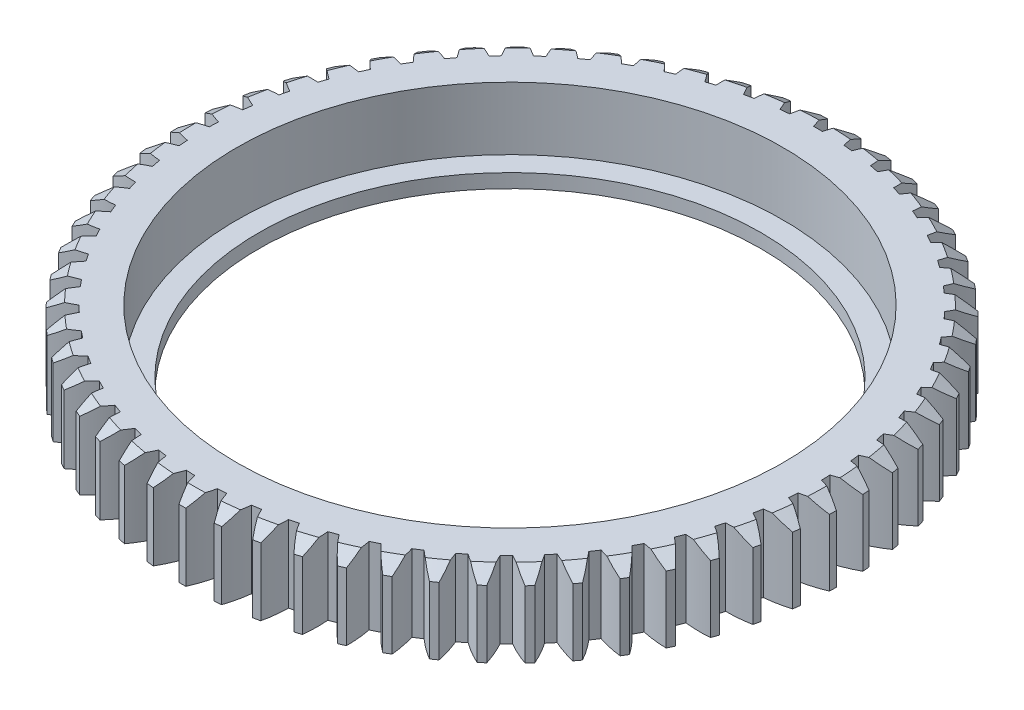
SolidWorks part; units mm, degrees
ref_plane "Front Plane" through (0, 0, 0) normal (0, 0, 1) x (1, 0, 0)
ref_plane "Top Plane" through (0, 0, 0) normal (0, 1, 0) x (1, 0, 0)
ref_plane "Right Plane" through (0, 0, 0) normal (1, 0, 0) x (0, 0, -1)
sketch "Sketch1" plane through (0, 0, 0) normal (0, 1, 0) x (1, 0, 0)
  circle A0 centre (0, 0) radius 47.5
  dimension "D1" = 95
extrude "Boss-Extrude1" add sketch "Sketch1" along normal blind 11 contours A0
sketch "Sketch2" plane through (0, 11, 0) normal (0, 1, 0) x (1, 0, 0)
  circle A0 centre (0, 0) radius 39.15
  dimension "D1" = 78.3
extrude "Cut-Extrude1" cut sketch "Sketch2" against normal blind 9 contours A0
sketch "Sketch3" plane through (0, 2, 0) normal (0, 1, 0) x (1, 0, 0)
  circle A0 centre (0, 0) radius 36
  dimension "D1" = 72
extrude "Cut-Extrude2" cut sketch "Sketch3" against normal through all
sketch "Sketch4" plane through (0, 11, 0) normal (0, 1, 0) x (1, 0, 0)
  arc A0 (-46.9496, 3.2406) -> (-43.6435, 1.852) centre (-38.2442, 19.3373) ccw
  arc A1 (-43.6435, 1.852) -> (-43.6763, 0.577) centre (0.1949, 0.0849) ccw
  arc A2 (-43.6763, 0.577) -> (-47.0495, -0.6396) centre (-39.1843, -17.1632) ccw
  arc A3 (-47.0495, -0.6396) -> (-47.0242, -1.6236) centre (0.1949, 0.0849) ccw
  arc A4 (-47.0242, -1.6236) -> (-43.5928, -2.6649) centre (-40.02, 15.2829) ccw
  arc A5 (-43.5928, -2.6649) -> (-43.4944, -3.9365) centre (0.1949, 0.0849) ccw
  arc A6 (-43.4944, -3.9365) -> (-46.7246, -5.4935) centre (-37.2021, -21.1208) ccw
  arc A7 (-46.7246, -5.4935) -> (-46.5982, -6.4697) centre (0.1949, 0.0849) ccw
  arc A8 (-46.5982, -6.4697) -> (-43.078, -7.1526) centre (-41.3695, 11.0675) ccw
  arc A9 (-43.078, -7.1526) -> (-42.8493, -8.4074) centre (0.1949, 0.0849) ccw
  arc A10 (-42.8493, -8.4074) -> (-45.9023, -10.2882) centre (-34.8235, -24.8536) ccw
  arc A11 (-45.9023, -10.2882) -> (-45.6763, -11.2463) centre (0.1949, 0.0849) ccw
  arc A12 (-45.6763, -11.2463) -> (-42.1045, -11.5636) centre (-42.2785, 6.7355) ccw
  arc A13 (-42.1045, -11.5636) -> (-41.748, -12.7882) centre (0.1949, 0.0849) ccw
  arc A14 (-41.748, -12.7882) -> (-44.5914, -14.973) centre (-32.0737, -28.322) ccw
  arc A15 (-44.5914, -14.973) -> (-44.268, -15.9027) centre (0.1949, 0.0849) ccw
  arc A16 (-44.268, -15.9027) -> (-40.6825, -15.8512) centre (-42.7372, 2.3331) ccw
  arc A17 (-40.6825, -15.8512) -> (-40.202, -17.0326) centre (0.1949, 0.0849) ccw
  arc A18 (-40.202, -17.0326) -> (-42.8058, -19.4982) centre (-28.9818, -31.4894) ccw
  arc A19 (-42.8058, -19.4982) -> (-42.3885, -20.3897) centre (0.1949, 0.0849) ccw
  arc A20 (-42.3885, -20.3897) -> (-38.8273, -19.9698) centre (-42.7408, -2.0931) ccw
  arc A21 (-38.8273, -19.9698) -> (-38.2279, -21.0956) centre (0.1949, 0.0849) ccw
  arc A22 (-38.2279, -21.0956) -> (-40.5643, -23.8158) centre (-25.5807, -34.322) ccw
  arc A23 (-40.5643, -23.8158) -> (-40.0576, -24.6597) centre (0.1949, 0.0849) ccw
  arc A24 (-40.0576, -24.6597) -> (-36.5585, -23.8758) centre (-42.2893, -6.4963) ccw
  arc A25 (-36.5585, -23.8758) -> (-35.8465, -24.934) centre (0.1949, 0.0849) ccw
  arc A26 (-35.8465, -24.934) -> (-37.8908, -27.88) centre (-21.9063, -36.7899) ccw
  arc A27 (-37.8908, -27.88) -> (-37.3, -28.6673) centre (0.1949, 0.0849) ccw
  arc A28 (-37.3, -28.6673) -> (-33.9, -27.5278) centre (-41.3874, -10.8296) ccw
  arc A29 (-33.9, -27.5278) -> (-33.083, -28.5072) centre (0.1949, 0.0849) ccw
  arc A30 (-33.083, -28.5072) -> (-34.8136, -31.6478) centre (-17.9977, -38.867) ccw
  arc A31 (-34.8136, -31.6478) -> (-34.1449, -32.3702) centre (0.1949, 0.0849) ccw
  arc A32 (-34.1449, -32.3702) -> (-30.8801, -30.8871) centre (-40.0448, -15.0473) ccw
  arc A33 (-30.8801, -30.8871) -> (-29.9667, -31.7773) centre (0.1949, 0.0849) ccw
  arc A34 (-29.9667, -31.7773) -> (-31.3652, -35.0792) centre (-13.8962, -40.5311) ccw
  arc A35 (-31.3652, -35.0792) -> (-30.6259, -35.729) centre (0.1949, 0.0849) ccw
  arc A36 (-30.6259, -35.729) -> (-27.5308, -33.9181) centre (-38.2756, -19.1046) ccw
  arc A37 (-27.5308, -33.9181) -> (-26.5307, -34.7097) centre (0.1949, 0.0849) ccw
  arc A38 (-26.5307, -34.7097) -> (-27.5823, -38.1379) centre (-9.6453, -41.7647) ccw
  arc A39 (-27.5823, -38.1379) -> (-26.7801, -38.7083) centre (0.1949, 0.0849) ccw
  arc A40 (-26.7801, -38.7083) -> (-23.8877, -36.5887) centre (-36.0986, -22.9585) ccw
  arc A41 (-23.8877, -36.5887) -> (-22.8115, -37.2732) centre (0.1949, 0.0849) ccw
  arc A42 (-22.8115, -37.2732) -> (-23.505, -40.7914) centre (-5.2902, -42.5547) ccw
  arc A43 (-23.505, -40.7914) -> (-22.6484, -41.2762) centre (0.1949, 0.0849) ccw
  arc A44 (-22.6484, -41.2762) -> (-19.9892, -38.8705) centre (-33.5369, -26.5681) ccw
  arc A45 (-19.9892, -38.8705) -> (-18.8483, -39.4408) centre (0.1949, 0.0849) ccw
  arc A46 (-18.8483, -39.4408) -> (-19.1765, -43.0116) centre (-0.8768, -42.8927) ccw
  arc A47 (-19.1765, -43.0116) -> (-18.2745, -43.4058) centre (0.1949, 0.0849) ccw
  arc A48 (-18.2745, -43.4058) -> (-15.8768, -40.7394) centre (-30.6176, -29.8952) ccw
  arc A49 (-15.8768, -40.7394) -> (-14.6833, -41.1893) centre (0.1949, 0.0849) ccw
  arc A50 (-14.6833, -41.1893) -> (-14.6426, -44.775) centre (3.5478, -42.7751) ccw
  arc A51 (-14.6426, -44.775) -> (-13.7048, -45.0743) centre (0.1949, 0.0849) ccw
  arc A52 (-13.7048, -45.0743) -> (-11.594, -42.1756) centre (-27.3717, -32.9045) ccw
  arc A53 (-11.594, -42.1756) -> (-10.3606, -42.5004) centre (0.1949, 0.0849) ccw
  arc A54 (-10.3606, -42.5004) -> (-9.9514, -46.0628) centre (7.937, -42.2032) ccw
  arc A55 (-9.9514, -46.0628) -> (-8.9878, -46.2642) centre (0.1949, 0.0849) ccw
  arc A56 (-8.9878, -46.2642) -> (-7.1863, -43.1637) centre (-23.8336, -35.564) ccw
  arc A57 (-7.1863, -43.1637) -> (-5.926, -43.36) centre (0.1949, 0.0849) ccw
  arc A58 (-5.926, -43.36) -> (-5.1526, -46.8615) centre (12.244, -41.183) ccw
  arc A59 (-5.1526, -46.8615) -> (-4.1735, -46.9627) centre (0.1949, 0.0849) ccw
  arc A60 (-4.1735, -46.9627) -> (-2.7003, -43.6934) centre (-20.0408, -37.8457) ccw
  arc A61 (-2.7003, -43.6934) -> (-1.4265, -43.7591) centre (0.1949, 0.0849) ccw
  arc A62 (-1.4265, -43.7591) -> (-0.2972, -47.1625) centre (16.4234, -39.7254) ccw
  arc A63 (-0.2972, -47.1625) -> (0.6871, -47.1625) centre (0.1949, 0.0849) ccw
  arc A64 (0.6871, -47.1625) -> (1.8164, -43.7591) centre (-16.0335, -39.7254) ccw
  arc A65 (1.8164, -43.7591) -> (3.0902, -43.6934) centre (0.1949, 0.0849) ccw
  arc A66 (3.0902, -43.6934) -> (4.5634, -46.9627) centre (20.4307, -37.8457) ccw
  arc A67 (4.5634, -46.9627) -> (5.5425, -46.8615) centre (0.1949, 0.0849) ccw
  arc A68 (5.5425, -46.8615) -> (6.3159, -43.36) centre (-11.8541, -41.183) ccw
  arc A69 (6.3159, -43.36) -> (7.5762, -43.1637) centre (0.1949, 0.0849) ccw
  arc A70 (7.5762, -43.1637) -> (9.3777, -46.2642) centre (24.2235, -35.564) ccw
  arc A71 (9.3777, -46.2642) -> (10.3413, -46.0628) centre (0.1949, 0.0849) ccw
  arc A72 (10.3413, -46.0628) -> (10.7505, -42.5004) centre (-7.5471, -42.2032) ccw
  arc A73 (10.7505, -42.5004) -> (11.9839, -42.1756) centre (0.1949, 0.0849) ccw
  arc A74 (11.9839, -42.1756) -> (14.0947, -45.0743) centre (27.7616, -32.9045) ccw
  arc A75 (14.0947, -45.0743) -> (15.0325, -44.775) centre (0.1949, 0.0849) ccw
  arc A76 (15.0325, -44.775) -> (15.0732, -41.1893) centre (-3.1579, -42.7751) ccw
  arc A77 (15.0732, -41.1893) -> (16.2667, -40.7394) centre (0.1949, 0.0849) ccw
  arc A78 (16.2667, -40.7394) -> (18.6644, -43.4058) centre (31.0075, -29.8952) ccw
  arc A79 (18.6644, -43.4058) -> (19.5664, -43.0116) centre (0.1949, 0.0849) ccw
  arc A80 (19.5664, -43.0116) -> (19.2382, -39.4408) centre (1.2667, -42.8927) ccw
  arc A81 (19.2382, -39.4408) -> (20.3791, -38.8705) centre (0.1949, 0.0849) ccw
  arc A82 (20.3791, -38.8705) -> (23.0383, -41.2762) centre (33.9268, -26.5681) ccw
  arc A83 (23.0383, -41.2762) -> (23.8949, -40.7914) centre (0.1949, 0.0849) ccw
  arc A84 (23.8949, -40.7914) -> (23.2014, -37.2732) centre (5.6801, -42.5547) ccw
  arc A85 (23.2014, -37.2732) -> (24.2776, -36.5887) centre (0.1949, 0.0849) ccw
  arc A86 (24.2776, -36.5887) -> (27.17, -38.7083) centre (36.4885, -22.9585) ccw
  arc A87 (27.17, -38.7083) -> (27.9722, -38.1379) centre (0.1949, 0.0849) ccw
  arc A88 (27.9722, -38.1379) -> (26.9206, -34.7097) centre (10.0352, -41.7647) ccw
  arc A89 (26.9206, -34.7097) -> (27.9207, -33.9181) centre (0.1949, 0.0849) ccw
  arc A90 (27.9207, -33.9181) -> (31.0158, -35.729) centre (38.6655, -19.1046) ccw
  arc A91 (31.0158, -35.729) -> (31.7551, -35.0792) centre (0.1949, 0.0849) ccw
  arc A92 (31.7551, -35.0792) -> (30.3566, -31.7773) centre (14.2861, -40.5311) ccw
  arc A93 (30.3566, -31.7773) -> (31.27, -30.8871) centre (0.1949, 0.0849) ccw
  arc A94 (31.27, -30.8871) -> (34.5348, -32.3702) centre (40.4347, -15.0473) ccw
  arc A95 (34.5348, -32.3702) -> (35.2035, -31.6478) centre (0.1949, 0.0849) ccw
  arc A96 (35.2035, -31.6478) -> (33.4729, -28.5072) centre (18.3876, -38.867) ccw
  arc A97 (33.4729, -28.5072) -> (34.2899, -27.5278) centre (0.1949, 0.0849) ccw
  arc A98 (34.2899, -27.5278) -> (37.6899, -28.6673) centre (41.7773, -10.8296) ccw
  arc A99 (37.6899, -28.6673) -> (38.2807, -27.88) centre (0.1949, 0.0849) ccw
  arc A100 (38.2807, -27.88) -> (36.2363, -24.934) centre (22.2962, -36.7899) ccw
  arc A101 (36.2363, -24.934) -> (36.9484, -23.8758) centre (0.1949, 0.0849) ccw
  arc A102 (36.9484, -23.8758) -> (40.4475, -24.6597) centre (42.6792, -6.4963) ccw
  arc A103 (40.4475, -24.6597) -> (40.9542, -23.8158) centre (0.1949, 0.0849) ccw
  arc A104 (40.9542, -23.8158) -> (38.6178, -21.0956) centre (25.9706, -34.322) ccw
  arc A105 (38.6178, -21.0956) -> (39.2172, -19.9698) centre (0.1949, 0.0849) ccw
  arc A106 (39.2172, -19.9698) -> (42.7784, -20.3897) centre (43.1307, -2.0931) ccw
  arc A107 (42.7784, -20.3897) -> (43.1957, -19.4982) centre (0.1949, 0.0849) ccw
  arc A108 (43.1957, -19.4982) -> (40.5919, -17.0326) centre (29.3717, -31.4894) ccw
  arc A109 (40.5919, -17.0326) -> (41.0724, -15.8512) centre (0.1949, 0.0849) ccw
  arc A110 (41.0724, -15.8512) -> (44.6579, -15.9027) centre (43.1271, 2.3331) ccw
  arc A111 (44.6579, -15.9027) -> (44.9813, -14.973) centre (0.1949, 0.0849) ccw
  arc A112 (44.9813, -14.973) -> (42.1379, -12.7882) centre (32.4636, -28.322) ccw
  arc A113 (42.1379, -12.7882) -> (42.4943, -11.5636) centre (0.1949, 0.0849) ccw
  arc A114 (42.4943, -11.5636) -> (46.0661, -11.2463) centre (42.6684, 6.7355) ccw
  arc A115 (46.0661, -11.2463) -> (46.2922, -10.2882) centre (0.1949, 0.0849) ccw
  arc A116 (46.2922, -10.2882) -> (43.2392, -8.4074) centre (35.2134, -24.8536) ccw
  arc A117 (43.2392, -8.4074) -> (43.4679, -7.1526) centre (0.1949, 0.0849) ccw
  arc A118 (43.4679, -7.1526) -> (46.9881, -6.4697) centre (41.7594, 11.0675) ccw
  arc A119 (46.9881, -6.4697) -> (47.1145, -5.4935) centre (0.1949, 0.0849) ccw
  arc A120 (47.1145, -5.4935) -> (43.8843, -3.9365) centre (37.592, -21.1208) ccw
  arc A121 (43.8843, -3.9365) -> (43.9827, -2.6649) centre (0.1949, 0.0849) ccw
  arc A122 (43.9827, -2.6649) -> (47.414, -1.6236) centre (40.4099, 15.2829) ccw
  arc A123 (47.414, -1.6236) -> (47.4394, -0.6396) centre (0.1949, 0.0849) ccw
  arc A124 (47.4394, -0.6396) -> (44.0662, 0.577) centre (39.5742, -17.1632) ccw
  arc A125 (44.0662, 0.577) -> (44.0333, 1.852) centre (0.1949, 0.0849) ccw
  arc A126 (44.0333, 1.852) -> (47.3395, 3.2406) centre (38.6341, 19.3373) ccw
  arc A127 (47.3395, 3.2406) -> (47.2635, 4.222) centre (0.1949, 0.0849) ccw
  arc A128 (47.2635, 4.222) -> (43.7831, 5.0852) centre (41.1389, -13.0227) ccw
  arc A129 (43.7831, 5.0852) -> (43.6193, 6.3501) centre (0.1949, 0.0849) ccw
  arc A130 (43.6193, 6.3501) -> (46.7651, 8.0713) centre (36.4508, 23.1876) ccw
  arc A131 (46.7651, 8.0713) -> (46.5886, 9.0397) centre (0.1949, 0.0849) ccw
  arc A132 (46.5886, 9.0397) -> (43.0379, 9.5405) centre (42.2697, -8.7434) ccw
  arc A133 (43.0379, 9.5405) -> (42.745, 10.7818) centre (0.1949, 0.0849) ccw
  arc A134 (42.745, 10.7818) -> (45.6971, 12.8173) centre (33.8832, 26.7931) ccw
  arc A135 (45.6971, 12.8173) -> (45.422, 13.7625) centre (0.1949, 0.0849) ccw
  arc A136 (45.422, 13.7625) -> (41.8386, 13.8955) centre (42.9544, -4.3704) ccw
  arc A137 (41.8386, 13.8955) -> (41.4196, 15.1002) centre (0.1949, 0.0849) ccw
  arc A138 (41.4196, 15.1002) -> (44.1468, 17.4284) centre (30.9585, 30.1154) ccw
  arc A139 (44.1468, 17.4284) -> (43.776, 18.3403) centre (0.1949, 0.0849) ccw
  arc A140 (43.776, 18.3403) -> (40.1979, 18.1042) centre (43.1859, 0.0498) ccw
  arc A141 (40.1979, 18.1042) -> (39.6572, 19.2594) centre (0.1949, 0.0849) ccw
  arc A142 (39.6572, 19.2594) -> (42.1306, 21.8557) centre (27.7077, 33.1193) ccw
  arc A143 (42.1306, 21.8557) -> (41.6679, 22.7245) centre (0.1949, 0.0849) ccw
  arc A144 (41.6679, 22.7245) -> (38.1331, 22.1218) centre (42.9616, 4.4703) ccw
  arc A145 (38.1331, 22.1218) -> (37.4765, 23.2153) centre (0.1949, 0.0849) ccw
  arc A146 (37.4765, 23.2153) -> (39.6698, 26.0522) centre (24.1652, 35.7731) ccw
  arc A147 (39.6698, 26.0522) -> (39.1203, 26.8688) centre (0.1949, 0.0849) ccw
  arc A148 (39.1203, 26.8688) -> (35.6662, 25.9059) centre (42.284, 8.8444) ccw
  arc A149 (35.6662, 25.9059) -> (34.9006, 26.926) centre (0.1949, 0.0849) ccw
  arc A150 (34.9006, 26.926) -> (36.7906, 29.9734) centre (20.3687, 38.0486) ccw
  arc A151 (36.7906, 29.9734) -> (36.16, 30.7292) centre (0.1949, 0.0849) ccw
  arc A152 (36.16, 30.7292) -> (32.8232, 29.4162) centre (41.1603, 13.1256) ccw
  arc A153 (32.8232, 29.4162) -> (31.9568, 30.3522) centre (0.1949, 0.0849) ccw
  arc A154 (31.9568, 30.3522) -> (33.5235, 33.5778) centre (16.3583, 39.9217) ccw
  arc A155 (33.5235, 33.5778) -> (32.8185, 34.2648) centre (0.1949, 0.0849) ccw
  arc A156 (32.8185, 34.2648) -> (29.6344, 32.6156) centre (39.6023, 17.2686) ccw
  arc A157 (29.6344, 32.6156) -> (28.6764, 33.4576) centre (0.1949, 0.0849) ccw
  arc A158 (28.6764, 33.4576) -> (29.9031, 36.8271) centre (12.1766, 41.3725) ccw
  arc A159 (29.9031, 36.8271) -> (29.1312, 37.438) centre (0.1949, 0.0849) ccw
  arc A160 (29.1312, 37.438) -> (26.1335, 35.4702) centre (37.6266, 21.2294) ccw
  arc A161 (26.1335, 35.4702) -> (25.094, 36.2092) centre (0.1949, 0.0849) ccw
  arc A162 (25.094, 36.2092) -> (25.9678, 39.687) centre (7.8678, 42.3856) ccw
  arc A163 (25.9678, 39.687) -> (25.1372, 40.2153) centre (0.1949, 0.0849) ccw
  arc A164 (25.1372, 40.2153) -> (22.3577, 37.9497) centre (35.2541, 24.9661) ccw
  arc A165 (22.3577, 37.9497) -> (21.2477, 38.5779) centre (0.1949, 0.0849) ccw
  arc A166 (21.2477, 38.5779) -> (21.7592, 42.1271) centre (3.4778, 42.9503) ccw
  arc A167 (21.7592, 42.1271) -> (20.8787, 42.5672) centre (0.1949, 0.0849) ccw
  arc A168 (20.8787, 42.5672) -> (18.347, 40.0278) centre (32.51, 28.4391) ccw
  arc A169 (18.347, 40.0278) -> (17.1783, 40.5385) centre (0.1949, 0.0849) ccw
  arc A170 (17.1783, 40.5385) -> (17.3221, 44.1215) centre (-0.9471, 43.0607) ccw
  arc A171 (17.3221, 44.1215) -> (16.401, 44.4688) centre (0.1949, 0.0849) ccw
  arc A172 (16.401, 44.4688) -> (14.1438, 41.6825) centre (29.4233, 31.6115) ccw
  arc A173 (14.1438, 41.6825) -> (12.9288, 42.0704) centre (0.1949, 0.0849) ccw
  arc A174 (12.9288, 42.0704) -> (12.7035, 45.6492) centre (-5.3599, 42.7155) ccw
  arc A175 (12.7035, 45.6492) -> (11.7516, 45.8998) centre (0.1949, 0.0849) ccw
  arc A176 (11.7516, 45.8998) -> (9.7928, 42.8962) centre (26.0268, 34.4497) ccw
  arc A177 (9.7928, 42.8962) -> (8.5443, 43.1571) centre (0.1949, 0.0849) ccw
  arc A178 (8.5443, 43.1571) -> (7.9522, 46.6938) centre (-9.7137, 41.9184) ccw
  arc A179 (7.9522, 46.6938) -> (6.9796, 46.8453) centre (0.1949, 0.0849) ccw
  arc A180 (6.9796, 46.8453) -> (5.34, 43.6562) centre (22.3565, 36.9236) ccw
  arc A181 (5.34, 43.6562) -> (4.0713, 43.7873) centre (0.1949, 0.0849) ccw
  arc A182 (4.0713, 43.7873) -> (3.1187, 47.2444) centre (-13.9626, 40.6778) ccw
  arc A183 (3.1187, 47.2444) -> (2.1357, 47.295) centre (0.1949, 0.0849) ccw
  arc A184 (2.1357, 47.295) -> (0.8327, 43.9543) centre (18.4512, 39.007) ccw
  arc A185 (0.8327, 43.9543) -> (-0.4428, 43.9543) centre (0.1949, 0.0849) ccw
  arc A186 (-0.4428, 43.9543) -> (-1.7458, 47.295) centre (-18.0614, 39.007) ccw
  arc A187 (-1.7458, 47.295) -> (-2.7288, 47.2444) centre (0.1949, 0.0849) ccw
  arc A188 (-2.7288, 47.2444) -> (-3.6814, 43.7873) centre (14.3525, 40.6778) ccw
  arc A189 (-3.6814, 43.7873) -> (-4.9501, 43.6562) centre (0.1949, 0.0849) ccw
  arc A190 (-4.9501, 43.6562) -> (-6.5897, 46.8453) centre (-21.9666, 36.9236) ccw
  arc A191 (-6.5897, 46.8453) -> (-7.5623, 46.6938) centre (0.1949, 0.0849) ccw
  arc A192 (-7.5623, 46.6938) -> (-8.1544, 43.1571) centre (10.1036, 41.9184) ccw
  arc A193 (-8.1544, 43.1571) -> (-9.4029, 42.8962) centre (0.1949, 0.0849) ccw
  arc A194 (-9.4029, 42.8962) -> (-11.3617, 45.8998) centre (-25.6369, 34.4497) ccw
  arc A195 (-11.3617, 45.8998) -> (-12.3136, 45.6492) centre (0.1949, 0.0849) ccw
  arc A196 (-12.3136, 45.6492) -> (-12.5389, 42.0704) centre (5.7498, 42.7155) ccw
  arc A197 (-12.5389, 42.0704) -> (-13.7539, 41.6825) centre (0.1949, 0.0849) ccw
  arc A198 (-13.7539, 41.6825) -> (-16.0111, 44.4688) centre (-29.0334, 31.6115) ccw
  arc A199 (-16.0111, 44.4688) -> (-16.9322, 44.1215) centre (0.1949, 0.0849) ccw
  arc A200 (-16.9322, 44.1215) -> (-16.7884, 40.5385) centre (1.337, 43.0607) ccw
  arc A201 (-16.7884, 40.5385) -> (-17.9571, 40.0278) centre (0.1949, 0.0849) ccw
  arc A202 (-17.9571, 40.0278) -> (-20.4888, 42.5672) centre (-32.1201, 28.4391) ccw
  arc A203 (-20.4888, 42.5672) -> (-21.3693, 42.1271) centre (0.1949, 0.0849) ccw
  arc A204 (-21.3693, 42.1271) -> (-20.8578, 38.5779) centre (-3.0879, 42.9503) ccw
  arc A205 (-20.8578, 38.5779) -> (-21.9678, 37.9497) centre (0.1949, 0.0849) ccw
  arc A206 (-21.9678, 37.9497) -> (-24.7473, 40.2153) centre (-34.8642, 24.9661) ccw
  arc A207 (-24.7473, 40.2153) -> (-25.5779, 39.687) centre (0.1949, 0.0849) ccw
  arc A208 (-25.5779, 39.687) -> (-24.7041, 36.2092) centre (-7.4779, 42.3856) ccw
  arc A209 (-24.7041, 36.2092) -> (-25.7436, 35.4702) centre (0.1949, 0.0849) ccw
  arc A210 (-25.7436, 35.4702) -> (-28.7413, 37.438) centre (-37.2367, 21.2294) ccw
  arc A211 (-28.7413, 37.438) -> (-29.5132, 36.8271) centre (0.1949, 0.0849) ccw
  arc A212 (-29.5132, 36.8271) -> (-28.2865, 33.4576) centre (-11.7867, 41.3725) ccw
  arc A213 (-28.2865, 33.4576) -> (-29.2445, 32.6156) centre (0.1949, 0.0849) ccw
  arc A214 (-29.2445, 32.6156) -> (-32.4287, 34.2648) centre (-39.2124, 17.2686) ccw
  arc A215 (-32.4287, 34.2648) -> (-33.1336, 33.5778) centre (0.1949, 0.0849) ccw
  arc A216 (-33.1336, 33.5778) -> (-31.5669, 30.3522) centre (-15.9684, 39.9217) ccw
  arc A217 (-31.5669, 30.3522) -> (-32.4333, 29.4162) centre (0.1949, 0.0849) ccw
  arc A218 (-32.4333, 29.4162) -> (-35.7702, 30.7292) centre (-40.7704, 13.1256) ccw
  arc A219 (-35.7702, 30.7292) -> (-36.4007, 29.9734) centre (0.1949, 0.0849) ccw
  arc A220 (-36.4007, 29.9734) -> (-34.5107, 26.926) centre (-19.9788, 38.0486) ccw
  arc A221 (-34.5107, 26.926) -> (-35.2763, 25.9059) centre (0.1949, 0.0849) ccw
  arc A222 (-35.2763, 25.9059) -> (-38.7304, 26.8688) centre (-41.8941, 8.8444) ccw
  arc A223 (-38.7304, 26.8688) -> (-39.2799, 26.0522) centre (0.1949, 0.0849) ccw
  arc A224 (-39.2799, 26.0522) -> (-37.0866, 23.2153) centre (-23.7753, 35.7731) ccw
  arc A225 (-37.0866, 23.2153) -> (-37.7432, 22.1218) centre (0.1949, 0.0849) ccw
  arc A226 (-37.7432, 22.1218) -> (-41.2781, 22.7245) centre (-42.5717, 4.4703) ccw
  arc A227 (-41.2781, 22.7245) -> (-41.7407, 21.8557) centre (0.1949, 0.0849) ccw
  arc A228 (-41.7407, 21.8557) -> (-39.2673, 19.2594) centre (-27.3178, 33.1193) ccw
  arc A229 (-39.2673, 19.2594) -> (-39.808, 18.1042) centre (0.1949, 0.0849) ccw
  arc A230 (-39.808, 18.1042) -> (-43.3861, 18.3403) centre (-42.796, 0.0498) ccw
  arc A231 (-43.3861, 18.3403) -> (-43.7569, 17.4284) centre (0.1949, 0.0849) ccw
  arc A232 (-43.7569, 17.4284) -> (-41.0297, 15.1002) centre (-30.5686, 30.1154) ccw
  arc A233 (-41.0297, 15.1002) -> (-41.4487, 13.8955) centre (0.1949, 0.0849) ccw
  arc A234 (-41.4487, 13.8955) -> (-45.0321, 13.7625) centre (-42.5645, -4.3704) ccw
  arc A235 (-45.0321, 13.7625) -> (-45.3072, 12.8173) centre (0.1949, 0.0849) ccw
  arc A236 (-45.3072, 12.8173) -> (-42.3551, 10.7818) centre (-33.4933, 26.7931) ccw
  arc A237 (-42.3551, 10.7818) -> (-42.648, 9.5405) centre (0.1949, 0.0849) ccw
  arc A238 (-42.648, 9.5405) -> (-46.1987, 9.0397) centre (-41.8798, -8.7434) ccw
  arc A239 (-46.1987, 9.0397) -> (-46.3752, 8.0713) centre (0.1949, 0.0849) ccw
  arc A240 (-46.3752, 8.0713) -> (-43.2294, 6.3501) centre (-36.0609, 23.1876) ccw
  arc A241 (-43.2294, 6.3501) -> (-43.3932, 5.0852) centre (0.1949, 0.0849) ccw
  arc A242 (-43.3932, 5.0852) -> (-46.8736, 4.222) centre (-40.749, -13.0227) ccw
  arc A243 (-46.8736, 4.222) -> (-46.9496, 3.2406) centre (0.1949, 0.0849) ccw
  circle A244 centre (0.1949, 0.0849) radius 56.4965
extrude "Cut-Extrude3" cut sketch "Sketch4" against normal through all
sketch "Sketch5" plane through (0, 11, 0) normal (0, 1, 0) x (1, 0, 0)
  circle A0 centre (0, 0) radius 36
  circle A1 centre (0, 0) radius 39
sketch "Sketch6" plane through (0, 0, 0) normal (1, 0, 0) x (0, 0, -1)
  line L5 (0, 0) -> (0, 19.1138) construction
  line L6 (-48.9761, 8.548) -> (-42.9101, 12.434)
  line L7 (-42.9101, 12.434) -> (-52.1039, 14.0453)
  line L8 (-52.1039, 14.0453) -> (-48.9761, 8.548)
revolve "Cut-Revolve2" cut sketch "Sketch6" angle 360 about L5
